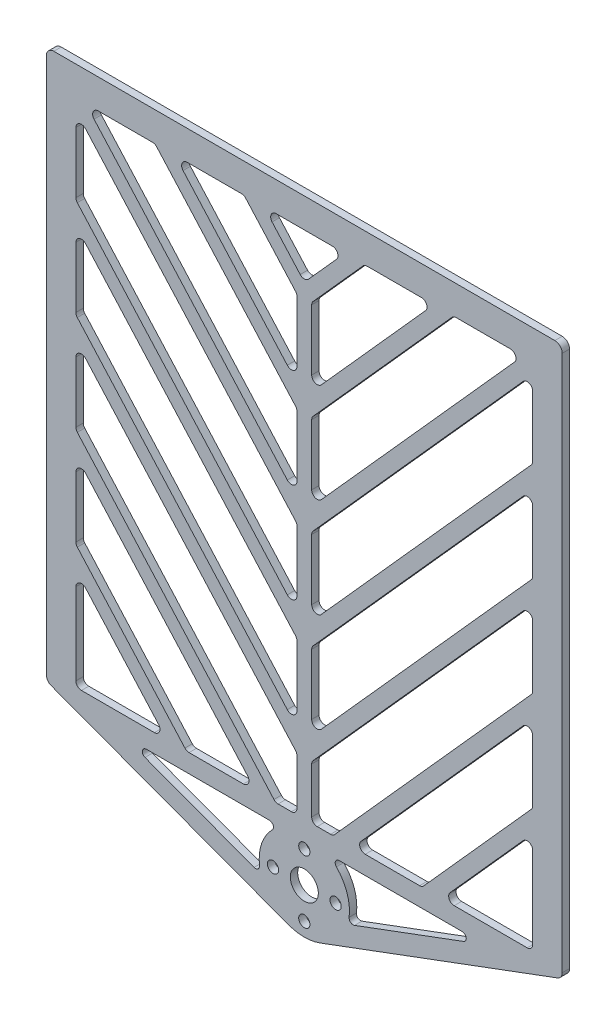
SolidWorks part; units mm, degrees
material "Thornel Mat VMA"
ref_plane "前视基准面" through (0, 0, 0) normal (0, 0, 1) x (1, 0, 0)
ref_plane "上视基准面" through (0, 0, 0) normal (0, 1, 0) x (1, 0, 0)
ref_plane "右视基准面" through (0, 0, 0) normal (1, 0, 0) x (0, 0, -1)
other "Configuration Table"
sketch "草图1" plane through (0, 0, 0) normal (0, 0, 1) x (1, 0, 0)
  line L1 (-70, -74.5) -> (70, -74.5)
  line L2 (-70, -74.5) -> (-70, 74.5)
  line L3 (-70, 74.5) -> (70, 74.5)
  line L4 (70, -74.5) -> (70, 74.5)
  line L5 (-70, -74.5) -> (70, 74.5) construction
  line L6 (-70, 74.5) -> (70, -74.5) construction
  point P0 (0, 0)
  dimension "D1" = 140
  dimension "D2" = 149
extrude "凸台-拉伸1" add sketch "草图1" along normal blind 2
sketch "草图2" plane through (0, 0, 2) normal (0, 0, 1) x (1, 0, 0)
  line L0 (0, 0) -> (0, -87.5) construction
  line L1 (-70, -74.5) -> (70, -74.5) construction
  line L2 (-70, -74.5) -> (-4.2757, -98.9796)
  line L3 (70, -74.5) -> (4.2757, -98.9796)
  line L4 (-70, -74.5) -> (70, -74.5)
  arc A0 (-4.2757, -98.9796) -> (4.2757, -98.9796) centre (0, -87.5) ccw
  dimension "D1" = 24.5
  dimension "D2" = 13
extrude "凸台-拉伸2" add sketch "草图2" against normal up to surface (2 mm away) up to face at (0, 0, 0)
fillet "圆角1" radius 2 4 edges at (70, -74.5, 1) (-70, -74.5, 1) (-70, 74.5, 1) (70, 74.5, 1)
sketch "草图4" plane through (0, 0, 0) normal (0, 0, -1) x (-1, 0, 0)
  circle A0 centre (-8.5, -87.5) radius 1.25 construction
  circle A1 centre (0, -79) radius 1.25 construction
  circle A2 centre (8.5, -87.5) radius 1.25 construction
  circle A3 centre (0, -96) radius 1.25 construction
  circle A4 centre (-8.5, -87.5) radius 1.25 construction
  circle A5 centre (0, -79) radius 1.25 construction
  circle A6 centre (8.5, -87.5) radius 1.25 construction
  circle A7 centre (0, -96) radius 1.25 construction
  circle A8 centre (8.5, -87.5) radius 1.525
  circle A9 centre (0, -96) radius 1.525
  circle A10 centre (-8.5, -87.5) radius 1.525
  circle A11 centre (0, -79) radius 1.525
  dimension "D1" = 3.05
extrude "切除-拉伸1" cut sketch "草图4" against normal up to surface (2 mm away) up to face at (0, -20.05, 2)
sketch "草图5" plane through (0, 0, 0) normal (0, 0, -1) x (-1, 0, 0)
  line L0 (-62, 66.5) -> (-62, -72)
  line L1 (-62, -72) -> (62, -72)
  line L2 (62, -72) -> (62, 66.5)
  line L3 (62, 66.5) -> (-62, 66.5)
  line L4 (-68, 74.5) -> (68, 74.5) construction
  line L5 (70, 72.5) -> (70, -73.1107) construction
  line L6 (-70, -73.1107) -> (-70, 72.5) construction
  line L7 (62, 66.5) -> (-62, -72) construction
  line L8 (60.5099, 67.8341) -> (-63.4901, -70.6659)
  line L9 (63.4901, 65.1659) -> (-60.5099, -73.3341)
  line L10 (62, 66.5) -> (81.995, 48.5984) construction
  line L11 (73.9205, 55.8275) -> (-50.0795, -82.6725)
  line L12 (76.9006, 53.1594) -> (-47.0994, -85.3406)
  line L13 (87.331, 43.821) -> (-36.669, -94.679)
  line L14 (90.3111, 41.1528) -> (-33.6889, -97.3472)
  line L15 (100.7416, 31.8144) -> (-23.2584, -106.6856)
  line L16 (103.7217, 29.1463) -> (-20.2783, -109.3537)
  line L17 (114.1521, 19.8079) -> (-9.8479, -118.6921)
  line L18 (117.1322, 17.1397) -> (-6.8678, -121.3603)
  line L19 (47.0994, 79.8406) -> (-76.9006, -58.6594)
  line L20 (50.0795, 77.1725) -> (-73.9205, -61.3275)
  line L21 (33.6889, 91.8472) -> (-90.3111, -46.6528)
  line L22 (36.669, 89.179) -> (-87.331, -49.321)
  line L23 (20.2783, 103.8537) -> (-103.7217, -34.6463)
  line L24 (23.2584, 101.1856) -> (-100.7416, -37.3144)
  line L25 (6.8678, 115.8603) -> (-117.1322, -22.6397)
  line L26 (9.8479, 113.1921) -> (-114.1521, -25.3079)
  line L27 (0, 66.5) -> (0, -72) construction
  line L28 (-2, 66.5) -> (-2, -72)
  line L29 (2, 66.5) -> (2, -72)
  circle A0 centre (0, -79) radius 1.525 construction
  arc A2 (60.5099, 67.8341) -> (63.4901, 65.1659) centre (62, 66.5) cw
  arc A3 (-63.4901, -70.6659) -> (-60.5099, -73.3341) centre (-62, -72) ccw
  arc A4 (-50.0795, -82.6725) -> (-47.0994, -85.3406) centre (-48.5895, -84.0066) ccw
  arc A5 (73.9205, 55.8275) -> (76.9006, 53.1594) centre (75.4105, 54.4934) cw
  arc A6 (-36.669, -94.679) -> (-33.6889, -97.3472) centre (-35.1789, -96.0131) ccw
  arc A7 (87.331, 43.821) -> (90.3111, 41.1528) centre (88.8211, 42.4869) cw
  arc A8 (-23.2584, -106.6856) -> (-20.2783, -109.3537) centre (-21.7684, -108.0197) ccw
  arc A9 (100.7416, 31.8144) -> (103.7217, 29.1463) centre (102.2316, 30.4803) cw
  arc A10 (-9.8479, -118.6921) -> (-6.8678, -121.3603) centre (-8.3578, -120.0262) ccw
  arc A11 (114.1521, 19.8079) -> (117.1322, 17.1397) centre (115.6422, 18.4738) cw
  arc A12 (-76.9006, -58.6594) -> (-73.9205, -61.3275) centre (-75.4105, -59.9934) ccw
  arc A13 (47.0994, 79.8406) -> (50.0795, 77.1725) centre (48.5895, 78.5066) cw
  arc A14 (-90.3111, -46.6528) -> (-87.331, -49.321) centre (-88.8211, -47.9869) ccw
  arc A15 (33.6889, 91.8472) -> (36.669, 89.179) centre (35.1789, 90.5131) cw
  arc A16 (-103.7217, -34.6463) -> (-100.7416, -37.3144) centre (-102.2316, -35.9803) ccw
  arc A17 (20.2783, 103.8537) -> (23.2584, 101.1856) centre (21.7684, 102.5197) cw
  arc A18 (-117.1322, -22.6397) -> (-114.1521, -25.3079) centre (-115.6422, -23.9738) ccw
  arc A19 (6.8678, 115.8603) -> (9.8479, 113.1921) centre (8.3578, 114.5262) cw
  arc A20 (-2, 66.5) -> (2, 66.5) centre (0, 66.5) cw
  arc A21 (-2, -72) -> (2, -72) centre (0, -72) ccw
  dimension "D1" = 8
  dimension "D2" = 8
  dimension "D3" = 8
  dimension "D4" = 7
  dimension "D8" = 36
  dimension "D10" = 18
  dimension "D5" = 2
  dimension "D6" = 2
  dimension "D11" = 2
  dimension "D12" = 2
  dimension "D7" = 5
  dimension "D9" = 5
extrude "切除-拉伸3" cut sketch "草图5" against normal up to surface (2 mm away) contours L2 L18 L1 | L17 L2 L16 L1 | L14 L29 L1 L15 L2 | L12 L29 L13 L2 | L9 L29 L11 L2 | L20 L29 L8 L3 | L22 L29 L19 L3 up to face at (-10.025, -87.5, 2)
mirror "镜向1" about plane through (0, 0, 0) normal (1, 0, 0) of "切除-拉伸3"
sketch "草图6" plane through (0, 0, 2) normal (0, 0, 1) x (1, 0, 0)
  line L0 (-10.9954, 66.5) -> (10.9954, 66.5)
  line L1 (10.9954, 66.5) -> (0, 54.2189)
  line L2 (0, 54.2189) -> (-10.9954, 66.5)
  line L3 (0, 54.2189) -> (0, 0) construction
  line L4 (-2, 50.456) -> (-16.3643, 66.5) construction
  line L6 (2, 50.456) -> (16.3643, 66.5) construction
  line L7 (16.3643, 66.5) -> (35.1555, 66.5) construction
  dimension "D1" = 4
extrude "切除-拉伸4" cut sketch "草图6" against normal up to surface (2 mm away) up to face at (-32, -7.486, 0)
fillet "圆角3" radius 1.5 59 edges at (62, 36.5164, 1) (2, -30.4998, 1) (2, -51.4883, 1) (62, 15.5278, 1) (31.9559, -72, 1) (62, -38.4427, 1) (62, -17.4542, 1) (13.1647, -72, 1) (16.3643, 66.5, 1) (2, 50.456, 1) (2, 29.4675, 1) (35.1555, 66.5, 1) (62, -72, 1) (62, -44.4394, 1) (37.3248, -72, 1) (-62, 15.5278, 1) (-2, -51.4883, 1) (-2, -30.4998, 1) (-62, 36.5164, 1) (-62, 42.5131, 1) (-2, -24.503, 1) (-2, -3.5145, 1) (-62, 63.5016, 1) (-37.3248, -72, 1) (-62, -44.4394, 1) (-62, -72, 1) (-59.3155, 66.5, 1) (-2, 2.4822, 1) (-2, 23.4708, 1) (-40.5244, 66.5, 1) (-35.1555, 66.5, 1) (-2, 29.4675, 1) (-2, 50.456, 1) (-16.3643, 66.5, 1) (-62, -11.4574, 1) (-7.7958, -72, 1) (-62, 9.5311, 1) (-31.9559, -72, 1) (-13.1647, -72, 1) (-62, -17.4542, 1) (-62, -38.4427, 1) (40.5244, 66.5, 1) (2, 23.4708, 1) (2, 2.4822, 1) (59.3155, 66.5, 1) (62, 9.5311, 1) (2, -57.485, 1) (2, -72, 1) (7.7958, -72, 1) (62, -11.4574, 1) (62, 63.5016, 1) (2, -3.5145, 1) (2, -24.503, 1) (62, 42.5131, 1) (-10.9954, 66.5, 1) (0, 54.2189, 1) (10.9954, 66.5, 1) (-2, -57.485, 1) (-2, -72, 1)
sketch "草图7" plane through (0, 0, 0) normal (0, 0, -1) x (-1, 0, 0)
  circle A0 centre (0, -87.5) radius 3.8
  dimension "D1" = 7.6
extrude "切除-拉伸5" cut sketch "草图7" against normal blind 22
sketch "草图8" plane through (0, 0, 0) normal (0, 0, -1) x (-1, 0, 0)
  line L0 (48.9626, -77) -> (11.7837, -90.8476)
  line L1 (68.6981, -74.9849) -> (4.2757, -98.9796) construction
  line L2 (48.9626, -77) -> (6.3097, -77)
  line L3 (31.2855, -72) -> (16.521, -72) construction
  arc A0 (11.7837, -90.8476) -> (6.3097, -77) centre (0, -87.5) ccw
  dimension "D1" = 24.5
  dimension "D2" = 5
  dimension "D3" = 5
extrude "切除-拉伸6" cut sketch "草图8" against normal blind 22
mirror "镜向2" about plane through (0, 0, 0) normal (1, 0, 0) of "切除-拉伸6"
fillet "圆角4" radius 1.1 6 edges at (6.3097, -77, 1) (48.9626, -77, 1) (-6.3097, -77, 1) (-48.9626, -77, 1) (11.7837, -90.8476, 1) (-11.7837, -90.8476, 1)
